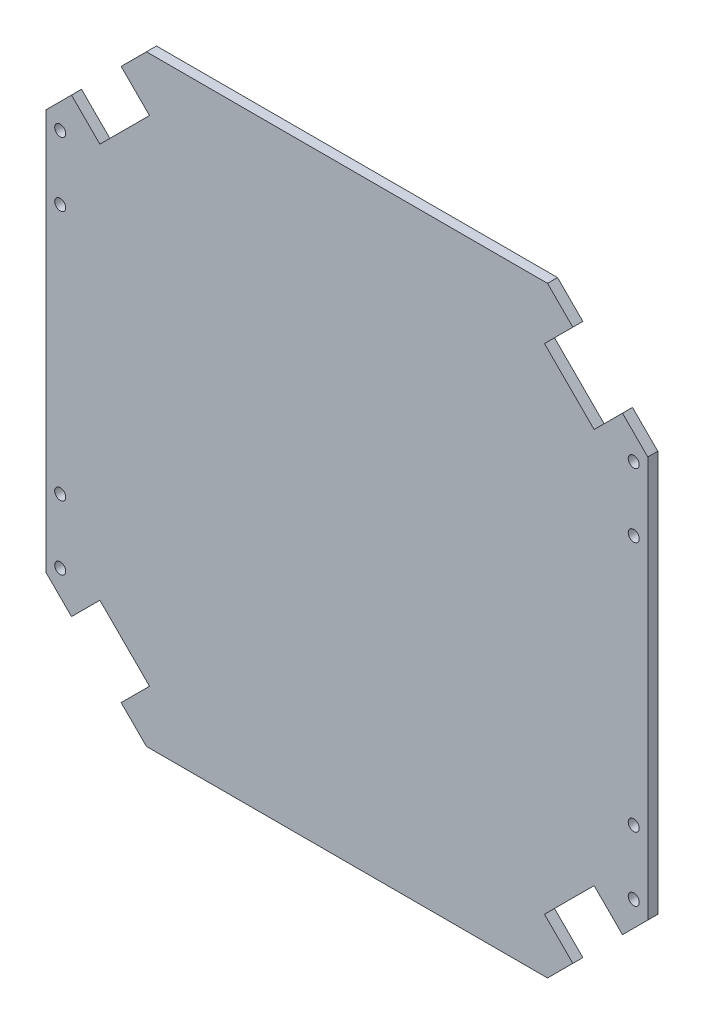
SolidWorks part; units mm, degrees
ref_plane "Plan de face" through (0, 0, 0) normal (0, 0, 1) x (1, 0, 0)
ref_plane "Plan de dessus" through (0, 0, 0) normal (0, 1, 0) x (1, 0, 0)
ref_plane "Plan de droite" through (0, 0, 0) normal (1, 0, 0) x (0, 0, -1)
sketch "Esquisse1" plane through (0, 0, 0) normal (0, 0, 1) x (1, 0, 0)
  line L0 (100, 150) -> (150, 100)
  line L1 (150, -150) -> (-150, -150)
  line L2 (150, -150) -> (150, 150)
  line L3 (150, 150) -> (-150, 150)
  line L4 (-150, -150) -> (-150, 150)
  line L5 (150, -150) -> (-150, 150) construction
  line L6 (150, 150) -> (-150, -150) construction
  line L7 (0, 237.159) -> (0, -197.6632) construction
  line L8 (-230.3021, 0) -> (257.9193, 0) construction
  line L9 (-100, 150) -> (-150, 100)
  line L10 (100, -150) -> (150, -100)
  line L11 (-100, -150) -> (-150, -100)
  line L22 (-137.3744, 112.6256) -> (-123.2322, 98.4835)
  line L23 (-123.2322, 98.4835) -> (-98.4835, 123.2322)
  line L24 (-98.4835, 123.2322) -> (-112.6256, 137.3744)
  line L25 (137.3744, 112.6256) -> (123.2322, 98.4835)
  line L26 (123.2322, 98.4835) -> (98.4835, 123.2322)
  line L27 (98.4835, 123.2322) -> (112.6256, 137.3744)
  line L28 (-137.3744, -112.6256) -> (-123.2322, -98.4835)
  line L29 (-123.2322, -98.4835) -> (-98.4835, -123.2322)
  line L30 (-98.4835, -123.2322) -> (-112.6256, -137.3744)
  line L31 (137.3744, -112.6256) -> (123.2322, -98.4835)
  line L32 (98.4835, -123.2322) -> (112.6256, -137.3744)
  line L33 (123.2322, -98.4835) -> (98.4835, -123.2322)
  point P0 (0, 0)
  point P18 (-90, 0)
  point P31 (-110.8579, 110.8579)
  dimension "D1" = 300
  dimension "D2" = 300
  dimension "D3" = 45
  dimension "D4" = 50
  dimension "D8" = 35
  dimension "D9" = 20
extrude "Boss.-Extru.1" add sketch "Esquisse1" along normal blind 5
sketch "Esquisse2" plane through (0, 0, 0) normal (0, 0, -1) x (-1, 0, 0)
  line L0 (-193.0928, 0) -> (181.779, 0) construction
  line L1 (-150, -100) -> (-150, 100) construction
  line L2 (150, -100) -> (150, 100) construction
  circle A8 centre (143, -62.5) radius 2.75
  circle A9 centre (143, -94.5) radius 2.75
  circle A10 centre (143, 62.5) radius 2.75
  circle A11 centre (143, 94.5) radius 2.75
  circle A12 centre (-143, -62.5) radius 2.75
  circle A13 centre (-143, -94.5) radius 2.75
  circle A14 centre (-143, 62.5) radius 2.75
  circle A15 centre (-143, 94.5) radius 2.75
  point P5 (0, 0)
  point P7 (0, 0)
  point P13 (0, 0)
  point P15 (0, 0)
  point P25 (0, 0)
  point P28 (0, 0)
  point P29 (0, 0)
  point P30 (0, 0)
  dimension "D1" = 5.5
  dimension "D2" = 5.5
  dimension "D6" = 5.5
  dimension "D7" = 5.5
  dimension "D11" = 5.5
  dimension "D12" = 5.5
  dimension "D17" = 5.5
  dimension "D18" = 5.5
  dimension "D3" = 32
  dimension "D4" = 7
  dimension "D5" = 62.5
  dimension "D8" = 32
  dimension "D9" = 62.5
  dimension "D10" = 7
  dimension "D13" = 32
  dimension "D14" = 62.5
  dimension "D15" = 62.5
  dimension "D16" = 32
extrude "Enlèv. mat.-Extru.1" cut sketch "Esquisse2" against normal through all
